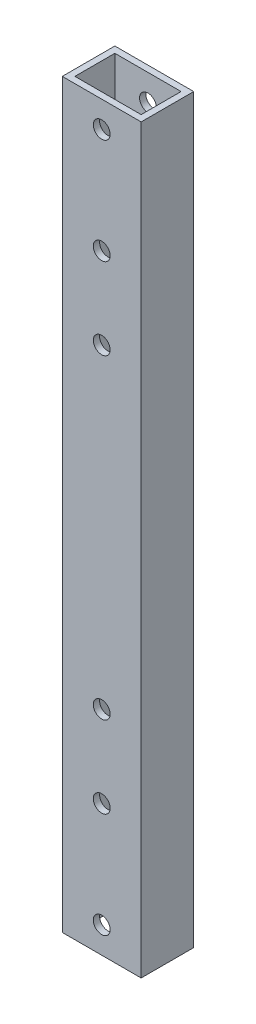
SolidWorks part; units mm, degrees
ref_plane "正面" through (0, 0, 0) normal (0, 0, 1) x (1, 0, 0)
ref_plane "平面" through (0, 0, 0) normal (0, 1, 0) x (1, 0, 0)
ref_plane "右側面" through (0, 0, 0) normal (1, 0, 0) x (0, 0, -1)
sketch "ｽｹｯﾁ1" plane through (0, 0, 0) normal (0, 1, 0) x (1, 0, 0)
  line L0 (-6.3, 3.8) -> (6.3, 3.8)
  line L1 (-7.5, 5) -> (7.5, 5)
  line L2 (-7.5, 5) -> (-7.5, -5)
  line L3 (-7.5, -5) -> (7.5, -5)
  line L4 (7.5, 5) -> (7.5, -5)
  line L5 (-7.5, 5) -> (7.5, -5) construction
  line L6 (-7.5, -5) -> (7.5, 5) construction
  line L7 (6.3, 3.8) -> (6.3, -3.8)
  line L8 (-6.3, -3.8) -> (6.3, -3.8)
  line L9 (-6.3, 3.8) -> (-6.3, -3.8)
  point P0 (0, 0)
  dimension "D1" = 15
  dimension "D2" = 10
  dimension "D3" = 1.2
extrude "ﾎﾞｽ - 押し出し1" add sketch "ｽｹｯﾁ1" along normal mid plane 141
sketch "ｽｹｯﾁ2" plane through (0, 0, -5) normal (0, 0, -1) x (-1, 0, 0)
  line L0 (0, 0) -> (-7.5, 0) construction
  line L1 (-7.5, 70.5) -> (-7.5, -70.5) construction
  line L2 (0, 0) -> (0, -70.5) construction
  line L3 (-7.5, -70.5) -> (7.5, -70.5) construction
  line L4 (0, 0) -> (0, -30) construction
  circle A0 centre (0, -65.5) radius 1.6
  circle A1 centre (0, -45.5) radius 1.6
  circle A2 centre (0, 45.5) radius 1.6
  circle A3 centre (0, 65.5) radius 1.6
  circle A4 centre (0, -30) radius 1.6
  circle A5 centre (0, 30) radius 1.6
  dimension "D1" = 3.2
  dimension "D2" = 3.2
  dimension "D6" = 3.2
  dimension "D3" = 5
  dimension "D4" = 20
  dimension "D5" = 30
extrude "ｶｯﾄ - 押し出し1" cut sketch "ｽｹｯﾁ2" against normal blind 100
